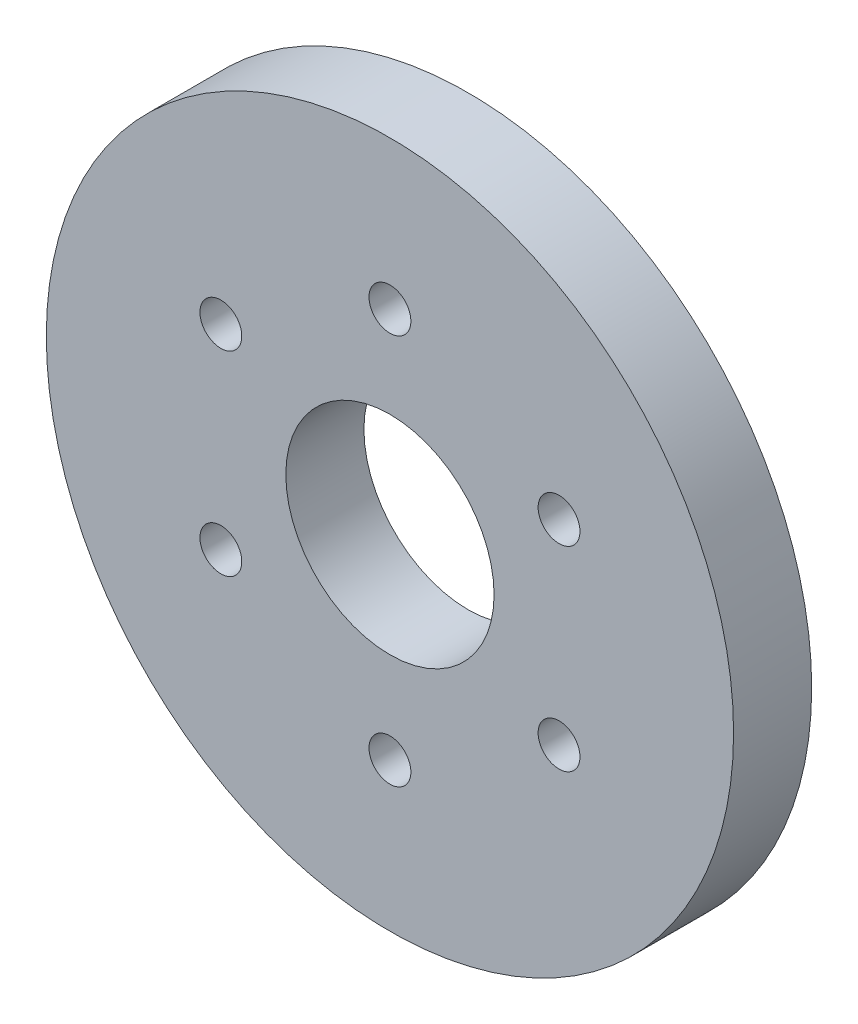
SolidWorks part; units mm, degrees
material "AISI 1020"
ref_plane "Front Plane" through (0, 0, 0) normal (0, 0, 1) x (1, 0, 0)
ref_plane "Top Plane" through (0, 0, 0) normal (0, 1, 0) x (1, 0, 0)
ref_plane "Right Plane" through (0, 0, 0) normal (1, 0, 0) x (0, 0, -1)
sketch "Sketch1" plane through (0, 0, 0) normal (0, 0, 1) x (1, 0, 0)
  line L0 (0, 0) -> (0, 23.8125) construction
  line L1 (0, 0) -> (20.6222, 11.9062) construction
  circle A0 centre (0, 0) radius 41.91
  circle A1 centre (0, 0) radius 23.8125 construction
  circle A2 centre (0, 23.8125) radius 2.5527
  circle A3 centre (20.6222, 11.9062) radius 2.5527
  circle A4 centre (20.6222, -11.9063) radius 2.5527
  circle A5 centre (0, -23.8125) radius 2.5527
  circle A6 centre (-20.6222, -11.9062) radius 2.5527
  circle A7 centre (-20.6222, 11.9063) radius 2.5527
  circle A8 centre (0, 0) radius 12.7
  dimension "D1" = 47.625
  dimension "D2" = 5.1054
  dimension "D5" = 83.82
  dimension "D4" = 25.4
  dimension "D3" = 60
extrude "Boss-Extrude1" add sketch "Sketch1" along normal blind 9.525
